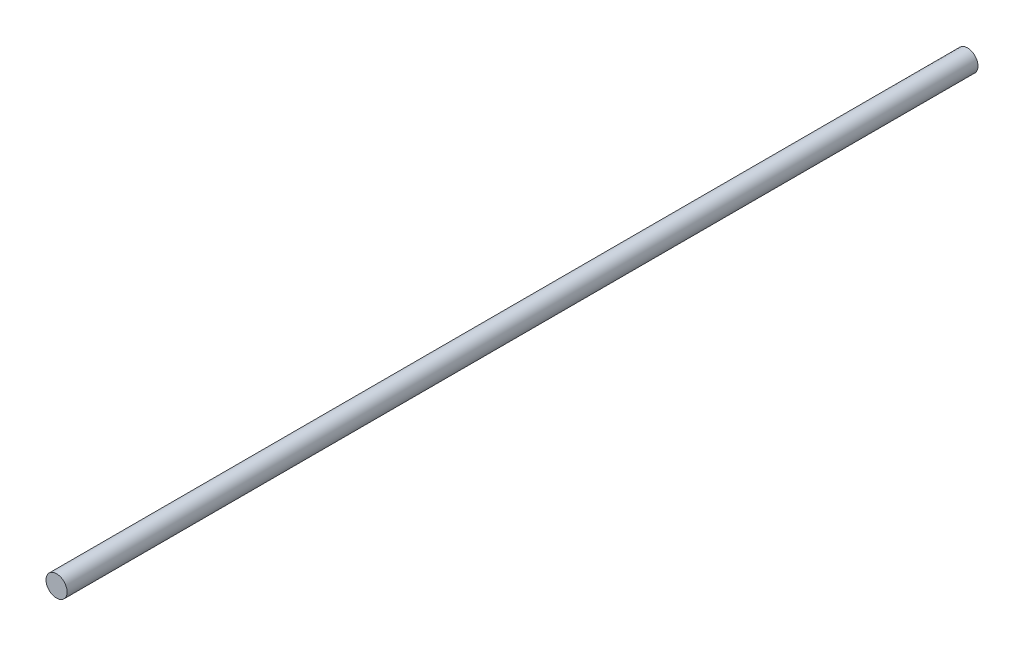
SolidWorks part; units mm, degrees
ref_plane "Front Plane" through (0, 0, 0) normal (0, 0, 1) x (1, 0, 0)
ref_plane "Top Plane" through (0, 0, 0) normal (0, 1, 0) x (1, 0, 0)
ref_plane "Right Plane" through (0, 0, 0) normal (1, 0, 0) x (0, 0, -1)
sketch "Sketch1" plane through (0, 0, 0) normal (0, 0, 1) x (1, 0, 0)
  circle A0 centre (0, 0) radius 4
  dimension "D1" = 8
extrude "Boss-Extrude1" add sketch "Sketch1" along normal blind 345
